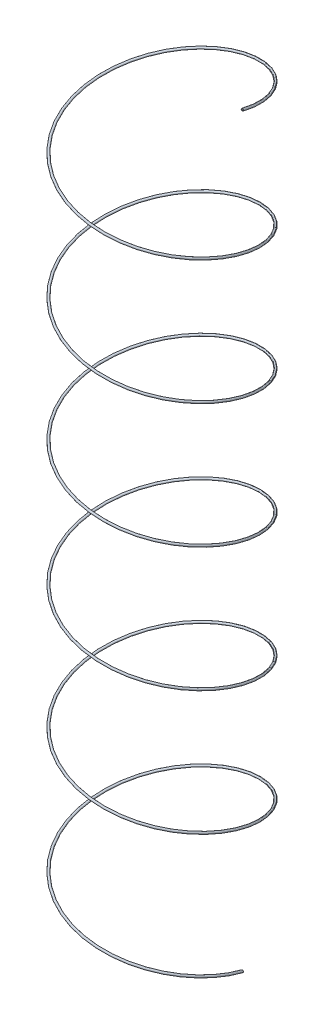
SolidWorks part; units mm, degrees
material "Резина"
ref_plane "Спереди" through (0, 0, 0) normal (0, 0, 1) x (1, 0, 0)
ref_plane "Сверху" through (0, 0, 0) normal (0, 1, 0) x (1, 0, 0)
ref_plane "Справа" through (0, 0, 0) normal (1, 0, 0) x (0, 0, -1)
sketch "Эскиз1" plane through (0, 0, 0) normal (0, 1, 0) x (1, 0, 0)
  line L0 (-127.5234, 0) -> (138.0228, 0) construction
  circle A0 centre (0, 0) radius 107.5
  dimension "D1" = 215
curve "Спираль1" pitch 166.3 height 997.8 turns 6
sketch "Эскиз3" plane through (0, 0, 0) normal (0, 0, 1) x (1, 0, 0)
  line L0 (107.5, 0) -> (-107.5, 0) construction
  line L1 (-127.5234, 0) -> (138.0228, 0) construction
  circle A0 centre (107.5, 0) radius 1.5
  circle A1 centre (107.5, 0) radius 1.13
  point P7 (107.5, 0)
  dimension "D1" = 3
  dimension "D2" = 2.26
sweep "По траектории1" add profiles "Эскиз3" path "Спираль1"
sketch "Эскиз4" plane through (0, 0, 0) normal (1, 0, 0) x (0, 0, -1)
  line L0 (107.5, 0) -> (-107.5, 0) construction
  line L1 (7.4329, 0) -> (-33.1497, 0)
  line L2 (7.4329, 0) -> (7.4329, -9.0125)
  line L3 (7.4329, -9.0125) -> (-33.1497, -9.0125)
  line L4 (-33.1497, 0) -> (-33.1497, -9.0125)
ref_plane "Плоскость1" through (107.5, 0, 0) normal (0, 0.2391, 0.971) x (1, 0, 0)
